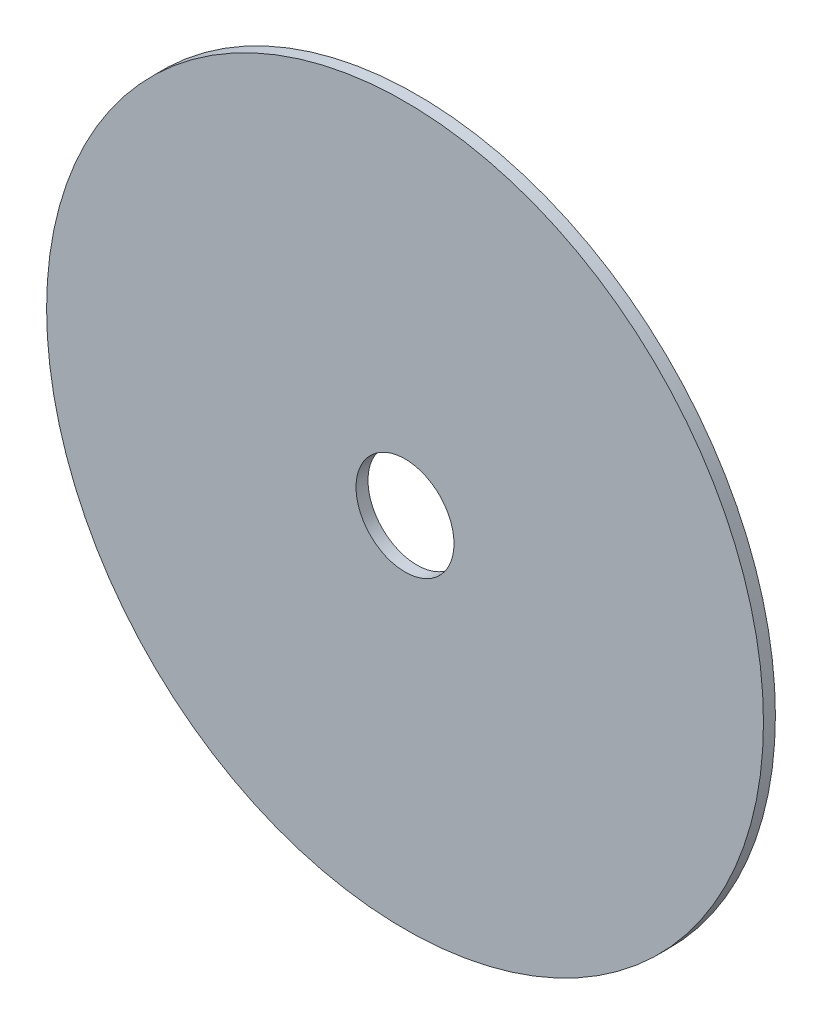
SolidWorks part; units mm, degrees
ref_plane "前视基准面" through (0, 0, 0) normal (0, 0, 1) x (1, 0, 0)
ref_plane "上视基准面" through (0, 0, 0) normal (0, 1, 0) x (1, 0, 0)
ref_plane "右视基准面" through (0, 0, 0) normal (1, 0, 0) x (0, 0, -1)
sketch "草图1" plane through (0, 0, 0) normal (0, 0, 1) x (1, 0, 0)
  circle A0 centre (0, 0) radius 4.1
  circle A1 centre (0, 0) radius 30
  dimension "D1" = 8.2
  dimension "D2" = 60
extrude "凸台-拉伸1" add sketch "草图1" along normal blind 1
